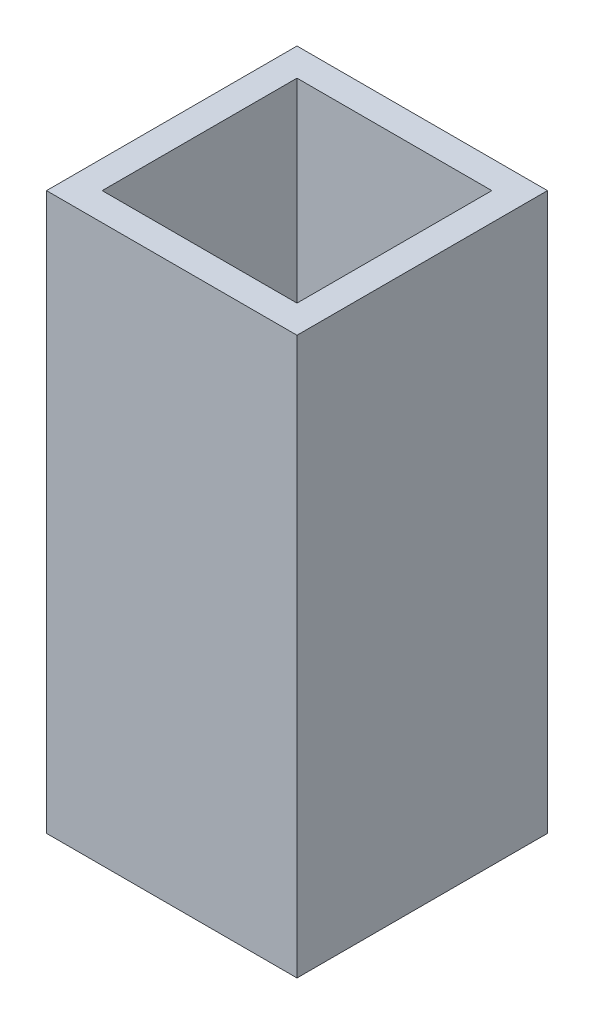
SolidWorks part; units mm, degrees
ref_plane "前视基准面" through (0, 0, 0) normal (0, 0, 1) x (1, 0, 0)
ref_plane "上视基准面" through (0, 0, 0) normal (0, 1, 0) x (1, 0, 0)
ref_plane "右视基准面" through (0, 0, 0) normal (1, 0, 0) x (0, 0, -1)
other "Configuration Table"
sketch "草图1" plane through (0, 0, 0) normal (0, 1, 0) x (1, 0, 0)
  line L1 (-1.75, 1.75) -> (1.75, 1.75)
  line L2 (-1.75, 1.75) -> (-1.75, -1.75)
  line L3 (-1.75, -1.75) -> (1.75, -1.75)
  line L4 (1.75, 1.75) -> (1.75, -1.75)
  line L5 (-1.75, 1.75) -> (1.75, -1.75) construction
  line L6 (-1.75, -1.75) -> (1.75, 1.75) construction
  line L7 (-2.25, 2.25) -> (2.25, 2.25)
  line L8 (-2.25, 2.25) -> (-2.25, -2.25)
  line L9 (-2.25, -2.25) -> (2.25, -2.25)
  line L10 (2.25, 2.25) -> (2.25, -2.25)
  line L11 (-2.25, 2.25) -> (2.25, -2.25) construction
  line L12 (-2.25, -2.25) -> (2.25, 2.25) construction
  point P0 (0, 0)
  point P6 (0, 0)
  dimension "D1" = 4.5
  dimension "D2" = 4.5
  dimension "D3" = 3.5
  dimension "D4" = 3.5
extrude "凸台-拉伸1" add sketch "草图1" along normal blind 10
